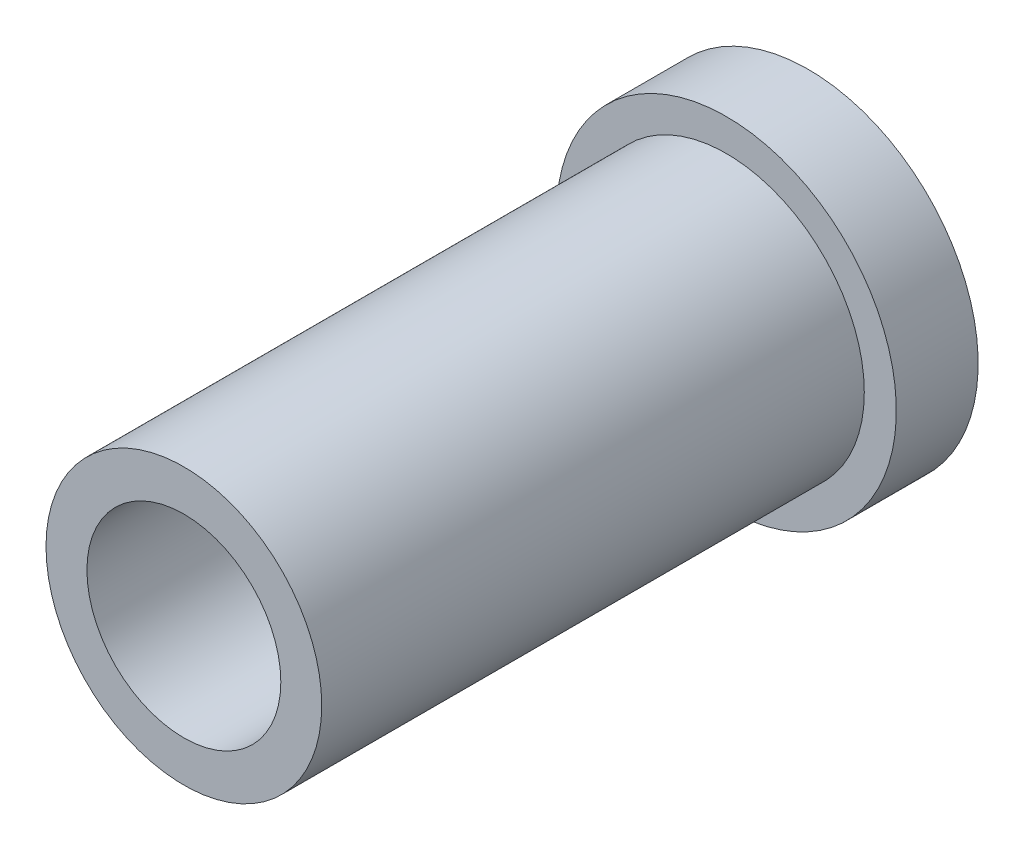
SolidWorks part; units mm, degrees
ref_plane "Front Plane" through (0, 0, 0) normal (0, 0, 1) x (1, 0, 0)
ref_plane "Top Plane" through (0, 0, 0) normal (0, 1, 0) x (1, 0, 0)
ref_plane "Right Plane" through (0, 0, 0) normal (1, 0, 0) x (0, 0, -1)
sketch "Sketch1" plane through (0, 0, 0) normal (0, 1, 0) x (1, 0, 0)
  line L0 (-0.545, 0.46) -> (-0.955, 0.46)
  line L1 (-0.955, 0.46) -> (-0.955, 0)
  line L2 (-0.955, 0) -> (-0.775, 0)
  line L3 (-0.775, 0) -> (-0.775, -3.05)
  line L4 (-0.775, -3.05) -> (-0.545, -3.05)
  line L5 (-0.545, -3.05) -> (-0.545, 0.46)
  line L6 (0, 0.46) -> (0, -3.05) construction
  dimension "D1" = 3.51
  dimension "D2" = 0.46
  dimension "D3" = 1.91
  dimension "D4" = 1.55
  dimension "D5" = 1.09
revolve "Revolve1" add sketch "Sketch1" angle 360 about L6
